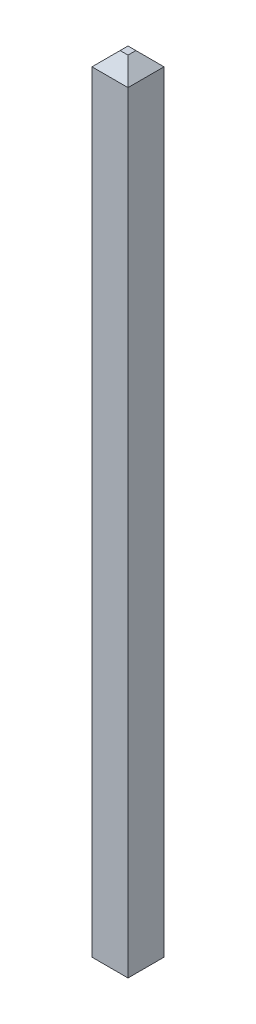
SolidWorks part; units mm, degrees
material "Czyste srebro"
ref_plane "Front Plane" through (0, 0, 0) normal (0, 0, 1) x (1, 0, 0)
ref_plane "Top Plane" through (0, 0, 0) normal (0, 1, 0) x (1, 0, 0)
ref_plane "Right Plane" through (0, 0, 0) normal (1, 0, 0) x (0, 0, -1)
sketch "Szkic1" plane through (0, 0, 0) normal (0, 1, 0) x (1, 0, 0)
  line L1 (-0.32, 0.32) -> (0.32, 0.32)
  line L2 (-0.32, 0.32) -> (-0.32, -0.32)
  line L3 (-0.32, -0.32) -> (0.32, -0.32)
  line L4 (0.32, 0.32) -> (0.32, -0.32)
  line L5 (-0.32, 0.32) -> (0.32, -0.32) construction
  line L6 (-0.32, -0.32) -> (0.32, 0.32) construction
  point P0 (0, 0)
extrude "Dodanie-wyciągnięcie1" add sketch "Szkic1" along normal blind 14.2 contours L1 L4 L3 L2
chamfer "Sfazowanie1" distance 0.25 angle 45 4 edges at (0.32, 14.2, 0) (0, 14.2, 0.32) (-0.32, 14.2, 0) (0, 14.2, -0.32)
chamfer "Sfazowanie2" distance 0.25 angle 45 4 edges at (0.32, 0, 0) (0, 0, -0.32) (-0.32, 0, 0) (0, 0, 0.32)
